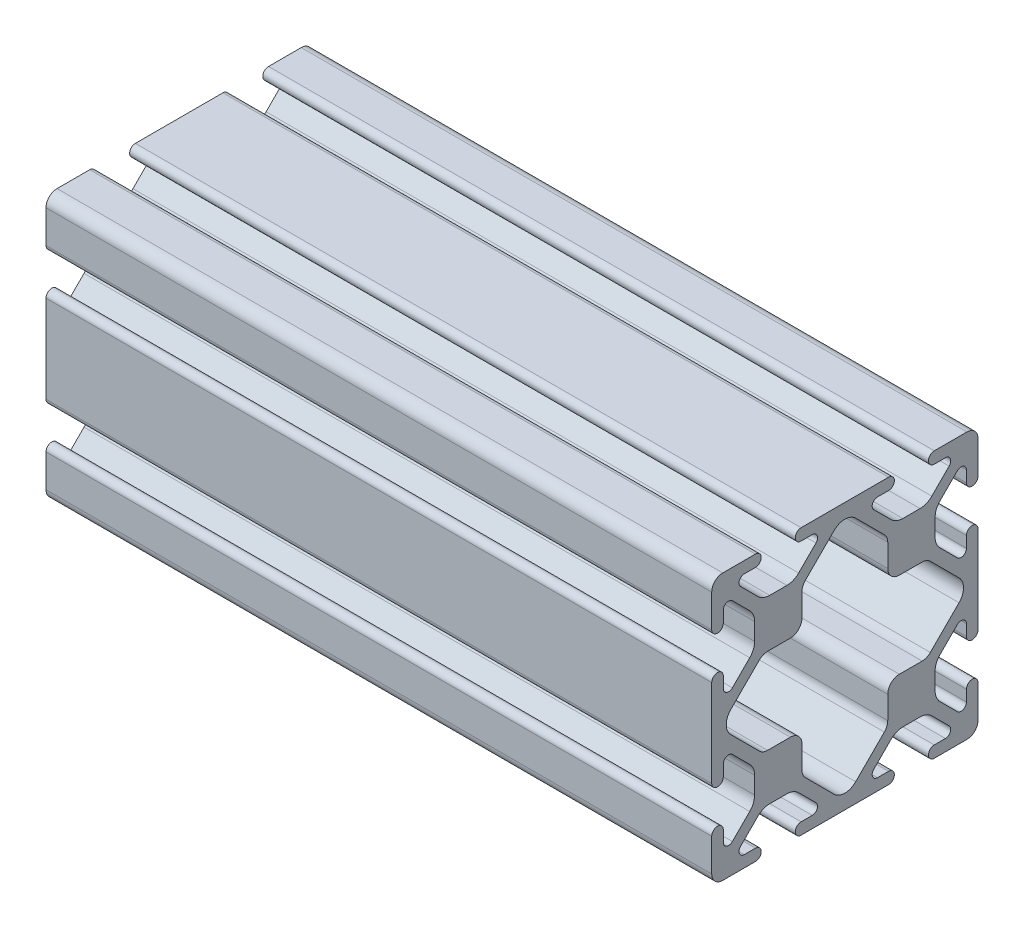
SolidWorks part; units mm, degrees
ref_plane "Front Plane" through (0, 0, 0) normal (0, 0, 1) x (1, 0, 0)
ref_plane "Top Plane" through (0, 0, 0) normal (0, 1, 0) x (1, 0, 0)
ref_plane "Right Plane" through (0, 0, 0) normal (1, 0, 0) x (0, 0, -1)
sketch "Sketch1" plane through (0, 0, 0) normal (1, 0, 0) x (0, 0, -1)
  line L0 (23.1902, 19.1749) -> (23.1902, 17.0561)
  line L1 (25.4, 17.0561) -> (25.4, 23.2918)
  line L2 (23.2918, 25.4) -> (17.0561, 25.4)
  line L3 (17.0561, 23.1902) -> (19.1749, 23.1902)
  line L4 (19.8933, 21.4558) -> (16.5846, 18.1471)
  line L5 (14.3396, 17.2172) -> (11.0604, 17.2172)
  line L6 (8.8154, 18.1471) -> (5.5067, 21.4558)
  line L7 (6.2251, 23.1902) -> (8.3439, 23.1902)
  line L8 (8.3439, 25.4) -> (-8.3439, 25.4)
  line L9 (-8.3439, 23.1902) -> (-6.2251, 23.1902)
  line L10 (-5.5067, 21.4558) -> (-8.8154, 18.1471)
  line L11 (-11.0604, 17.2172) -> (-14.3396, 17.2172)
  line L12 (-16.5846, 18.1471) -> (-19.8933, 21.4558)
  line L13 (-19.1749, 23.1902) -> (-17.0561, 23.1902)
  line L14 (-17.0561, 25.4) -> (-23.2918, 25.4)
  line L15 (-25.4, 23.2918) -> (-25.4, 17.0561)
  line L16 (-23.1902, 17.0561) -> (-23.1902, 19.1749)
  line L17 (-21.4558, 19.8933) -> (-18.1471, 16.5846)
  line L18 (-17.2172, 14.3396) -> (-17.2172, 11.0604)
  line L19 (-18.1471, 8.8154) -> (-21.4558, 5.5067)
  line L20 (-23.1902, 6.2251) -> (-23.1902, 8.3439)
  line L21 (-25.4, 8.3439) -> (-25.4, -8.3439)
  line L22 (-23.1902, -8.3439) -> (-23.1902, -6.2251)
  line L23 (-21.4558, -5.5067) -> (-18.1471, -8.8154)
  line L24 (-17.2172, -11.0604) -> (-17.2172, -14.3396)
  line L25 (-18.1471, -16.5846) -> (-21.4558, -19.8933)
  line L26 (-23.1902, -19.1749) -> (-23.1902, -17.0561)
  line L27 (-25.4, -17.0561) -> (-25.4, -23.2918)
  line L28 (-23.2918, -25.4) -> (-17.0561, -25.4)
  line L29 (-17.0561, -23.1902) -> (-19.1749, -23.1902)
  line L30 (-19.8933, -21.4558) -> (-16.5846, -18.1471)
  line L31 (-14.3396, -17.2172) -> (-11.0604, -17.2172)
  line L32 (-8.8154, -18.1471) -> (-5.5067, -21.4558)
  line L33 (-6.2251, -23.1902) -> (-8.3439, -23.1902)
  line L34 (-8.3439, -25.4) -> (8.3439, -25.4)
  line L35 (8.3439, -23.1902) -> (6.2251, -23.1902)
  line L36 (5.5067, -21.4558) -> (8.8154, -18.1471)
  line L37 (11.0604, -17.2172) -> (14.3396, -17.2172)
  line L38 (16.5846, -18.1471) -> (19.8933, -21.4558)
  line L39 (19.1749, -23.1902) -> (17.0561, -23.1902)
  line L40 (17.0561, -25.4) -> (23.2918, -25.4)
  line L41 (25.4, -23.2918) -> (25.4, -17.0561)
  line L42 (23.1902, -17.0561) -> (23.1902, -19.1749)
  line L43 (21.4558, -19.8933) -> (18.1471, -16.5846)
  line L44 (17.2172, -14.3396) -> (17.2172, -11.0604)
  line L45 (18.1471, -8.8154) -> (21.4558, -5.5067)
  line L46 (23.1902, -6.2251) -> (23.1902, -8.3439)
  line L47 (25.4, -8.3439) -> (25.4, 8.3439)
  line L48 (23.1902, 8.3439) -> (23.1902, 6.2251)
  line L49 (21.4558, 5.5067) -> (18.1471, 8.8154)
  line L50 (17.2172, 11.0604) -> (17.2172, 14.3396)
  line L51 (18.1471, 16.5846) -> (21.4558, 19.8933)
  line L84 (8.1828, -10.3926) -> (8.1828, -14.7392)
  line L85 (7.5356, -16.3017) -> (2.0587, -21.7787)
  line L86 (-2.0587, -21.7787) -> (-7.5356, -16.3017)
  line L87 (-8.1828, -14.7392) -> (-8.1828, -10.3926)
  line L88 (-10.3926, -8.1828) -> (-14.7392, -8.1828)
  line L89 (-16.3017, -7.5356) -> (-21.7787, -2.0587)
  line L90 (-21.7787, 2.0587) -> (-16.3017, 7.5356)
  line L91 (-14.7392, 8.1828) -> (-10.3926, 8.1828)
  line L92 (-8.1828, 10.3926) -> (-8.1828, 14.7392)
  line L93 (-7.5356, 16.3017) -> (-2.0587, 21.7787)
  line L94 (2.0587, 21.7787) -> (7.5356, 16.3017)
  line L95 (8.1828, 14.7392) -> (8.1828, 10.3926)
  line L96 (10.3926, 8.1828) -> (14.7392, 8.1828)
  line L97 (16.3017, 7.5356) -> (21.7787, 2.0587)
  line L98 (21.7787, -2.0587) -> (16.3017, -7.5356)
  line L99 (14.7392, -8.1828) -> (10.3926, -8.1828)
  arc A0 (21.4558, 19.8933) -> (23.1902, 19.1749) centre (22.1742, 19.1749) cw
  arc A1 (23.1902, 17.0561) -> (25.4, 17.0561) centre (24.2951, 17.0561) ccw
  arc A2 (25.4, 23.2918) -> (23.2918, 25.4) centre (23.2918, 23.2918) ccw
  arc A3 (17.0561, 25.4) -> (17.0561, 23.1902) centre (17.0561, 24.2951) ccw
  arc A4 (19.1749, 23.1902) -> (19.8933, 21.4558) centre (19.1749, 22.1742) cw
  arc A5 (16.5846, 18.1471) -> (14.3396, 17.2172) centre (14.3396, 20.3922) cw
  arc A6 (11.0604, 17.2172) -> (8.8154, 18.1471) centre (11.0604, 20.3922) cw
  arc A7 (5.5067, 21.4558) -> (6.2251, 23.1902) centre (6.2251, 22.1742) cw
  arc A8 (8.3439, 23.1902) -> (8.3439, 25.4) centre (8.3439, 24.2951) ccw
  arc A9 (-8.3439, 25.4) -> (-8.3439, 23.1902) centre (-8.3439, 24.2951) ccw
  arc A10 (-6.2251, 23.1902) -> (-5.5067, 21.4558) centre (-6.2251, 22.1742) cw
  arc A11 (-8.8154, 18.1471) -> (-11.0604, 17.2172) centre (-11.0604, 20.3922) cw
  arc A12 (-14.3396, 17.2172) -> (-16.5846, 18.1471) centre (-14.3396, 20.3922) cw
  arc A13 (-19.8933, 21.4558) -> (-19.1749, 23.1902) centre (-19.1749, 22.1742) cw
  arc A14 (-17.0561, 23.1902) -> (-17.0561, 25.4) centre (-17.0561, 24.2951) ccw
  arc A15 (-23.2918, 25.4) -> (-25.4, 23.2918) centre (-23.2918, 23.2918) ccw
  arc A16 (-25.4, 17.0561) -> (-23.1902, 17.0561) centre (-24.2951, 17.0561) ccw
  arc A17 (-23.1902, 19.1749) -> (-21.4558, 19.8933) centre (-22.1742, 19.1749) cw
  arc A18 (-18.1471, 16.5846) -> (-17.2172, 14.3396) centre (-20.3922, 14.3396) cw
  arc A19 (-17.2172, 11.0604) -> (-18.1471, 8.8154) centre (-20.3922, 11.0604) cw
  arc A20 (-21.4558, 5.5067) -> (-23.1902, 6.2251) centre (-22.1742, 6.2251) cw
  arc A21 (-23.1902, 8.3439) -> (-25.4, 8.3439) centre (-24.2951, 8.3439) ccw
  arc A22 (-25.4, -8.3439) -> (-23.1902, -8.3439) centre (-24.2951, -8.3439) ccw
  arc A23 (-23.1902, -6.2251) -> (-21.4558, -5.5067) centre (-22.1742, -6.2251) cw
  arc A24 (-18.1471, -8.8154) -> (-17.2172, -11.0604) centre (-20.3922, -11.0604) cw
  arc A25 (-17.2172, -14.3396) -> (-18.1471, -16.5846) centre (-20.3922, -14.3396) cw
  arc A26 (-21.4558, -19.8933) -> (-23.1902, -19.1749) centre (-22.1742, -19.1749) cw
  arc A27 (-23.1902, -17.0561) -> (-25.4, -17.0561) centre (-24.2951, -17.0561) ccw
  arc A28 (-25.4, -23.2918) -> (-23.2918, -25.4) centre (-23.2918, -23.2918) ccw
  arc A29 (-17.0561, -25.4) -> (-17.0561, -23.1902) centre (-17.0561, -24.2951) ccw
  arc A30 (-19.1749, -23.1902) -> (-19.8933, -21.4558) centre (-19.1749, -22.1742) cw
  arc A31 (-16.5846, -18.1471) -> (-14.3396, -17.2172) centre (-14.3396, -20.3922) cw
  arc A32 (-11.0604, -17.2172) -> (-8.8154, -18.1471) centre (-11.0604, -20.3922) cw
  arc A33 (-5.5067, -21.4558) -> (-6.2251, -23.1902) centre (-6.2251, -22.1742) cw
  arc A34 (-8.3439, -23.1902) -> (-8.3439, -25.4) centre (-8.3439, -24.2951) ccw
  arc A35 (8.3439, -25.4) -> (8.3439, -23.1902) centre (8.3439, -24.2951) ccw
  arc A36 (6.2251, -23.1902) -> (5.5067, -21.4558) centre (6.2251, -22.1742) cw
  arc A37 (8.8154, -18.1471) -> (11.0604, -17.2172) centre (11.0604, -20.3922) cw
  arc A38 (14.3396, -17.2172) -> (16.5846, -18.1471) centre (14.3396, -20.3922) cw
  arc A39 (19.8933, -21.4558) -> (19.1749, -23.1902) centre (19.1749, -22.1742) cw
  arc A40 (17.0561, -23.1902) -> (17.0561, -25.4) centre (17.0561, -24.2951) ccw
  arc A41 (23.2918, -25.4) -> (25.4, -23.2918) centre (23.2918, -23.2918) ccw
  arc A42 (25.4, -17.0561) -> (23.1902, -17.0561) centre (24.2951, -17.0561) ccw
  arc A43 (23.1902, -19.1749) -> (21.4558, -19.8933) centre (22.1742, -19.1749) cw
  arc A44 (18.1471, -16.5846) -> (17.2172, -14.3396) centre (20.3922, -14.3396) cw
  arc A45 (17.2172, -11.0604) -> (18.1471, -8.8154) centre (20.3922, -11.0604) cw
  arc A46 (21.4558, -5.5067) -> (23.1902, -6.2251) centre (22.1742, -6.2251) cw
  arc A47 (23.1902, -8.3439) -> (25.4, -8.3439) centre (24.2951, -8.3439) ccw
  arc A48 (25.4, 8.3439) -> (23.1902, 8.3439) centre (24.2951, 8.3439) ccw
  arc A49 (23.1902, 6.2251) -> (21.4558, 5.5067) centre (22.1742, 6.2251) cw
  arc A50 (18.1471, 8.8154) -> (17.2172, 11.0604) centre (20.3922, 11.0604) cw
  arc A51 (17.2172, 14.3396) -> (18.1471, 16.5846) centre (20.3922, 14.3396) cw
  arc A84 (10.3926, -8.1828) -> (8.1828, -10.3926) centre (10.3926, -10.3926) ccw
  arc A85 (8.1828, -14.7392) -> (7.5356, -16.3017) centre (5.973, -14.7392) cw
  arc A86 (2.0587, -21.7787) -> (-2.0587, -21.7787) centre (0, -19.72) cw
  arc A87 (-7.5356, -16.3017) -> (-8.1828, -14.7392) centre (-5.973, -14.7392) cw
  arc A88 (-8.1828, -10.3926) -> (-10.3926, -8.1828) centre (-10.3926, -10.3926) ccw
  arc A89 (-14.7392, -8.1828) -> (-16.3017, -7.5356) centre (-14.7392, -5.973) cw
  arc A90 (-21.7787, -2.0587) -> (-21.7787, 2.0587) centre (-19.72, 0) cw
  arc A91 (-16.3017, 7.5356) -> (-14.7392, 8.1828) centre (-14.7392, 5.973) cw
  arc A92 (-10.3926, 8.1828) -> (-8.1828, 10.3926) centre (-10.3926, 10.3926) ccw
  arc A93 (-8.1828, 14.7392) -> (-7.5356, 16.3017) centre (-5.973, 14.7392) cw
  arc A94 (-2.0587, 21.7787) -> (2.0587, 21.7787) centre (0, 19.72) cw
  arc A95 (7.5356, 16.3017) -> (8.1828, 14.7392) centre (5.973, 14.7392) cw
  arc A96 (8.1828, 10.3926) -> (10.3926, 8.1828) centre (10.3926, 10.3926) ccw
  arc A97 (14.7392, 8.1828) -> (16.3017, 7.5356) centre (14.7392, 5.973) cw
  arc A98 (21.7787, 2.0587) -> (21.7787, -2.0587) centre (19.72, 0) cw
  arc A99 (16.3017, -7.5356) -> (14.7392, -8.1828) centre (14.7392, -5.973) cw
extrude "Boss-Extrude1" add sketch "Sketch1" against normal blind 127
